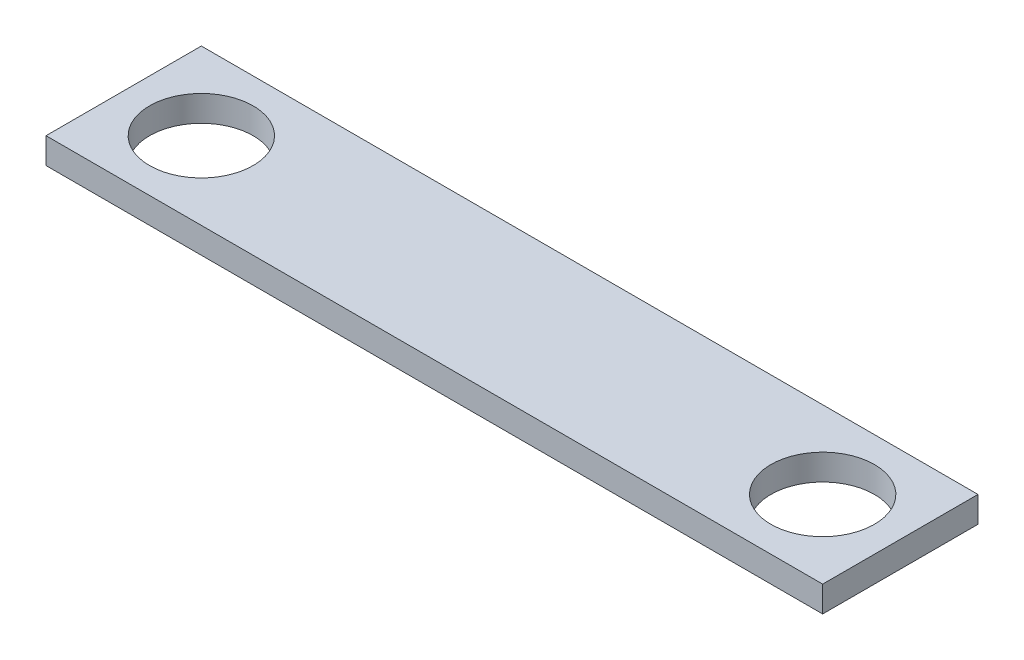
SolidWorks part; units mm, degrees
ref_plane "Front Plane" through (0, 0, 0) normal (0, 0, 1) x (1, 0, 0)
ref_plane "Top Plane" through (0, 0, 0) normal (0, 1, 0) x (1, 0, 0)
ref_plane "Right Plane" through (0, 0, 0) normal (1, 0, 0) x (0, 0, -1)
sketch "Sketch1" plane through (0, 0, 0) normal (0, 1, 0) x (1, 0, 0)
  line L1 (0, 0) -> (60, 0)
  line L2 (0, 0) -> (0, 12)
  line L3 (0, 12) -> (60, 12)
  line L4 (60, 0) -> (60, 12)
  dimension "D1" = 60
  dimension "D2" = 12
extrude "Boss-Extrude1" add sketch "Sketch1" along normal blind 2
sketch "Sketch2" plane through (0, 2, 0) normal (0, 1, 0) x (1, 0, 0)
  line L0 (0, 12) -> (0, 0) construction
  line L1 (60, 12) -> (0, 12) construction
  line L2 (30, 12) -> (30, 0) construction
  line L3 (0, 0) -> (60, 0) construction
  circle A0 centre (6, 6) radius 4
  circle A1 centre (54, 6) radius 4
  dimension "D1" = 8
  dimension "D2" = 6
  dimension "D3" = 6
extrude "Cut-Extrude1" cut sketch "Sketch2" against normal through all contours A0 | A1
